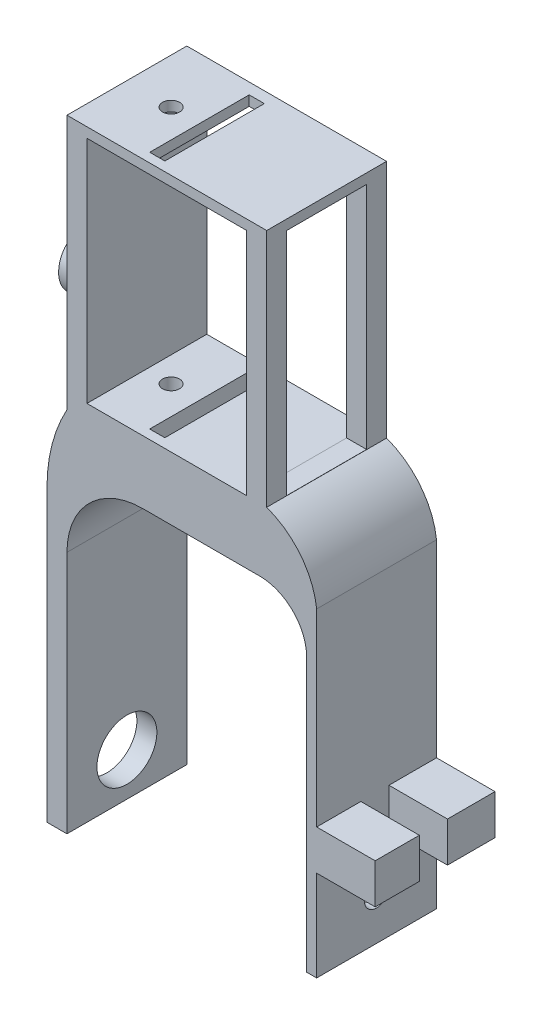
SolidWorks part; units mm, degrees
ref_plane "Front Plane" through (0, 0, 0) normal (0, 0, 1) x (1, 0, 0)
ref_plane "Top Plane" through (0, 0, 0) normal (0, 1, 0) x (1, 0, 0)
ref_plane "Right Plane" through (0, 0, 0) normal (1, 0, 0) x (0, 0, -1)
sketch "Sketch1" plane through (0, 0, 0) normal (0, 0, 1) x (1, 0, 0)
  line L0 (-1000, 0) -> (49000, 0) construction
  line L1 (0, -1000) -> (0, 49000) construction
  line L2 (-13.2583, -8.243) -> (-8.2583, -8.243)
  line L3 (-8.2583, -8.243) -> (-8.2583, 52.784)
  line L5 (51.7417, 60.019) -> (51.7417, -8.243)
  line L6 (51.7417, -8.243) -> (54.2417, -8.243)
  line L7 (54.2417, -8.243) -> (54.2417, 14.4914)
  line L8 (54.2417, 14.4914) -> (68.8861, 14.4914)
  line L9 (68.8861, 14.4914) -> (68.8861, 24.4914)
  line L10 (68.8861, 24.4914) -> (54.2417, 24.4914)
  line L11 (54.2417, 24.4914) -> (54.2417, 71.757)
  line L12 (41.7417, 87.5424) -> (41.7417, 147.5424)
  line L13 (41.7417, 147.5424) -> (-8.2583, 147.5424)
  line L15 (-13.2583, -8.243) -> (-13.2583, 64.3414)
  line L16 (-8.2583, 147.5424) -> (-8.2583, 83.6916)
  line L17 (10.7147, 71.757) -> (40.0037, 71.757)
  arc A0 (-8.2583, 52.784) -> (10.7147, 71.757) centre (10.7147, 52.784) cw
  arc A3 (-13.2583, 64.3414) -> (-8.2583, 83.6916) centre (26.6847, 64.3414) cw
  arc A4 (40.0037, 71.757) -> (51.7417, 60.019) centre (40.0037, 60.019) cw
  arc A5 (54.2417, 71.757) -> (41.7417, 87.5424) centre (35.1994, 69.5199) ccw
  dimension "D4" = 8.2583
  dimension "D5" = 15.7854
  dimension "D1" = 2.5
  dimension "D2" = 5
  dimension "D3" = 50
  dimension "D6" = 10
  dimension "D7" = 60
  dimension "D8" = 60
  dimension "D9" = 80
extrude "Boss-Extrude1" add sketch "Sketch1" against normal blind 30
sketch "Sketch8" plane through (41.7417, 0, 0) normal (1, 0, 0) x (0, 0, -1)
  line L4 (0, 147.5424) -> (0, 87.5424)
  line L5 (0, 87.5424) -> (30, 87.5424)
  line L6 (30, 87.5424) -> (30, 147.5424)
  line L7 (30, 147.5424) -> (0, 147.5424)
  line L8 (0, 147.5424) -> (0, 87.5424)
  line L10 (30, 87.5424) -> (30, 147.5424)
  line L11 (30, 147.5424) -> (0, 147.5424)
  line L12 (5, 87.5831) -> (25, 87.5831)
  line L13 (25, 87.5831) -> (25, 145.0424)
  line L14 (25, 145.0424) -> (5, 145.0424)
  line L15 (5, 145.0424) -> (5, 87.5831)
  line L20 (0, 87.5424) -> (30, 87.5424)
  dimension "D2" = 2.5
  dimension "D3" = 5
  dimension "D4" = 5
  dimension "D1" = 0
extrude "Cut-Extrude10" cut sketch "Sketch8" against normal blind 10
sketch "Sketch9" plane through (0, 0, 0) normal (0, 0, 1) x (1, 0, 0)
  line L0 (-3.2583, 145.0424) -> (-3.2583, 87.5572)
  line L1 (-3.2583, 87.5572) -> (36.7417, 87.5572)
  line L2 (-958.2583, 87.5424) -> (49041.7417, 87.5424) construction
  line L14 (-3.2583, 145.0424) -> (36.7417, 145.0424)
  line L15 (36.7417, 145.0424) -> (36.7417, 87.5572)
extrude "Cut-Extrude11" cut sketch "Sketch9" against normal through all
sketch "Sketch10" plane through (0, 147.5424, 0) normal (0, 1, 0) x (1, 0, 0)
  line L0 (10.137, 27.2142) -> (10.137, 2.3164)
  line L1 (10.137, 2.3164) -> (13.9244, 2.3164)
  line L2 (13.9244, 2.3164) -> (13.9244, 27.2142)
  line L3 (13.9244, 27.2142) -> (10.137, 27.2142)
extrude "Cut-Extrude12" cut sketch "Sketch10" against normal through all
sketch "Sketch11" plane through (-8.2583, 0, 0) normal (-1, 0, 0) x (0, 0, 1)
  line L0 (-30, 147.5424) -> (0, 147.5424) construction
  circle A0 centre (-15.4042, 104.5424) radius 7.5
  dimension "D1" = 15
  dimension "D2" = 43
extrude "Boss-Extrude3" add sketch "Sketch11" along normal blind 10
sketch "Sketch13" plane through (68.8861, 0, 0) normal (1, 0, 0) x (0, 0, -1)
  line L0 (11.0597, 24.4914) -> (11.0597, 14.4914)
  line L1 (30, 24.4914) -> (0, 24.4914) construction
  line L2 (30, 14.4914) -> (0, 14.4914) construction
  line L3 (11.0597, 14.4914) -> (18.0991, 14.4914)
  line L4 (18.0991, 14.4914) -> (18.0991, 24.4914)
  line L5 (18.0991, 24.4914) -> (11.0597, 24.4914)
extrude "Cut-Extrude13" cut sketch "Sketch13" against normal up to surface (14.6444 mm away) up to face at (54.2417, 48.1242, -15)
sketch "Sketch14" plane through (54.2417, 0, 0) normal (1, 0, 0) x (0, 0, -1)
  line L0 (15, -999.1766) -> (15, 49000.8234) construction
  line L4 (0, 14.4914) -> (0, -8.243)
  line L5 (0, -8.243) -> (30, -8.243)
  line L6 (30, -8.243) -> (30, 14.4914)
  line L7 (30, 14.4914) -> (18.0991, 14.4914)
  line L8 (0, 14.4914) -> (0, -8.243)
  line L9 (0, -8.243) -> (30, -8.243)
  line L10 (30, -8.243) -> (30, 14.4914)
  line L11 (30, 14.4914) -> (18.0991, 14.4914)
  line L21 (0, 71.757) -> (0, 24.4914)
  line L22 (0, 71.757) -> (0, 24.4914)
  line L23 (0, 24.4914) -> (11.0597, 24.4914)
  line L24 (0, 24.4914) -> (11.0597, 24.4914)
  line L25 (11.0597, 24.4914) -> (11.0597, 14.4914)
  line L26 (11.0597, 24.4914) -> (11.0597, 14.4914)
  line L27 (11.0597, 14.4914) -> (0, 14.4914)
  line L28 (11.0597, 14.4914) -> (0, 14.4914)
  line L29 (18.0991, 14.4914) -> (18.0991, 24.4914)
  line L30 (18.0991, 14.4914) -> (18.0991, 24.4914)
  line L31 (18.0991, 24.4914) -> (30, 24.4914)
  line L32 (18.0991, 24.4914) -> (30, 24.4914)
  line L33 (30, 24.4914) -> (30, 71.757)
  line L34 (30, 24.4914) -> (30, 71.757)
  line L35 (30, 71.757) -> (0, 71.757)
  line L37 (30, 71.757) -> (0, 71.757)
  circle A0 centre (15, 2.4914) radius 3.05
  point P2 (15, 2.4914)
  dimension "D2" = 6.1
  dimension "D3" = 12
  dimension "D1" = 0
extrude "Cut-Extrude14" cut sketch "Sketch14" against normal blind 10 contours A0 L0 | L0 A0
sketch "Sketch15" plane through (-13.2583, 0, 0) normal (-1, 0, 0) x (0, 0, 1)
  line L4 (0, -8.243) -> (0, 64.3414)
  line L5 (0, 64.3414) -> (-30, 64.3414)
  line L6 (-30, 64.3414) -> (-30, -8.243)
  line L7 (-30, -8.243) -> (0, -8.243)
  line L8 (0, -8.243) -> (0, 64.3414)
  line L9 (0, 64.3414) -> (-30, 64.3414)
  line L10 (-30, 64.3414) -> (-30, -8.243)
  line L11 (-30, -8.243) -> (0, -8.243)
  circle A0 centre (-15, 2.4914) radius 3.05 construction
  circle A1 centre (-15, 2.4914) radius 3.05
  circle A2 centre (-15, 2.4914) radius 7.5
  dimension "D2" = 15
  dimension "D1" = 0
extrude "Cut-Extrude15" cut sketch "Sketch15" against normal blind 10 contours A2 A1 | A1
sketch "Sketch16" plane through (0, 147.5424, 0) normal (0, 1, 0) x (1, 0, 0)
  line L4 (-8.2583, 0) -> (41.7417, 0)
  line L5 (41.7417, 0) -> (41.7417, 30)
  line L6 (41.7417, 30) -> (-8.2583, 30)
  line L7 (-8.2583, 30) -> (-8.2583, 0)
  line L8 (-8.2583, 0) -> (41.7417, 0)
  line L9 (41.7417, 0) -> (41.7417, 30)
  line L10 (41.7417, 30) -> (-8.2583, 30)
  line L11 (-8.2583, 30) -> (-8.2583, 0)
  circle A0 centre (3.0361, 14.7653) radius 2.125
  dimension "D2" = 4.25
  dimension "D1" = 0
extrude "Cut-Extrude16" cut sketch "Sketch16" against normal through all contours A0
